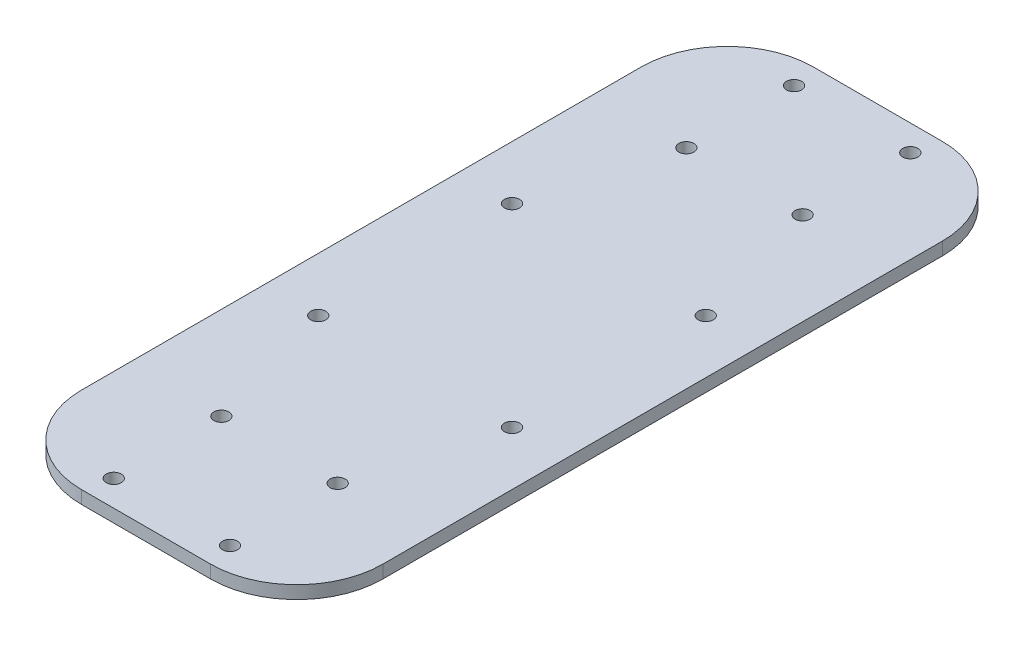
SolidWorks part; units mm, degrees
material "ABS"
ref_plane "Front Plane" through (0, 0, 0) normal (0, 0, 1) x (1, 0, 0)
ref_plane "Top Plane" through (0, 0, 0) normal (0, 1, 0) x (1, 0, 0)
ref_plane "Right Plane" through (0, 0, 0) normal (1, 0, 0) x (0, 0, -1)
sketch "Sketch1" plane through (0, 0, 0) normal (0, 1, 0) x (1, 0, 0)
  line L0 (-35, 0) -> (35, 0) construction
  line L1 (35, -85) -> (35, 85)
  line L2 (35, 85) -> (-35, 85)
  line L3 (-35, 85) -> (-35, -85)
  line L4 (-22.5, 22.5) -> (22.5, 22.5) construction
  line L5 (35, -85) -> (-35, -85)
  circle A0 centre (-22.5, 22.5) radius 1.75
  circle A1 centre (22.5, 22.5) radius 1.75
  circle A2 centre (-22.5, -22.5) radius 1.75
  circle A3 centre (22.5, -22.5) radius 1.75
  point P5 (0, 0)
  point P10 (0, 22.5)
  dimension "D4" = 3.5
  dimension "D1" = 85
  dimension "D2" = 70
  dimension "D3" = 45
  dimension "D5" = 22.5
extrude "Boss-Extrude1" add sketch "Sketch1" along normal blind 3
sketch "Sketch2" plane through (0, 0, 0) normal (0, 1, 0) x (1, 0, 0)
  line L0 (-35, -85) -> (35, -85) construction
  line L1 (35, -85) -> (35, 85) construction
  line L2 (-35, 85) -> (-35, -85) construction
  line L3 (35, 85) -> (-35, 85) construction
  line L4 (-35, -85) -> (35, -85) construction
  line L5 (35, -85) -> (35, 85) construction
  line L6 (-35, 85) -> (-35, -85) construction
  line L7 (35, 85) -> (-35, 85) construction
  line L8 (-35, 0) -> (35, 0) construction
  line L9 (-35, 28) -> (35, 28) construction
  line L10 (0, 28) -> (0, 85) construction
  line L11 (-13.5, 54) -> (-13.5, 79) construction
  line L12 (-13.5, 79) -> (13.5, 79) construction
  line L13 (13.5, 79) -> (13.5, 54) construction
  line L14 (13.5, 54) -> (-13.5, 54) construction
  circle A0 centre (-13.5, 79) radius 1.75
  circle A1 centre (13.5, 79) radius 1.75
  circle A2 centre (13.5, 54) radius 1.75
  circle A3 centre (-13.5, 54) radius 1.75
  point P18 (0, 79)
  dimension "D2" = 3.5
  dimension "D1" = 28
  dimension "D3" = 25
  dimension "D4" = 27
  dimension "D5" = 26
extrude "Cut-Extrude2" cut sketch "Sketch2" along normal through all
mirror "Mirror1" about plane through (0, 0, 0) normal (0, 0, 1) of "Cut-Extrude2"
fillet "Fillet1" radius 20 4 edges at (35, 1.5, -85) (-35, 1.5, -85) (-35, 1.5, 85) (35, 1.5, 85)
